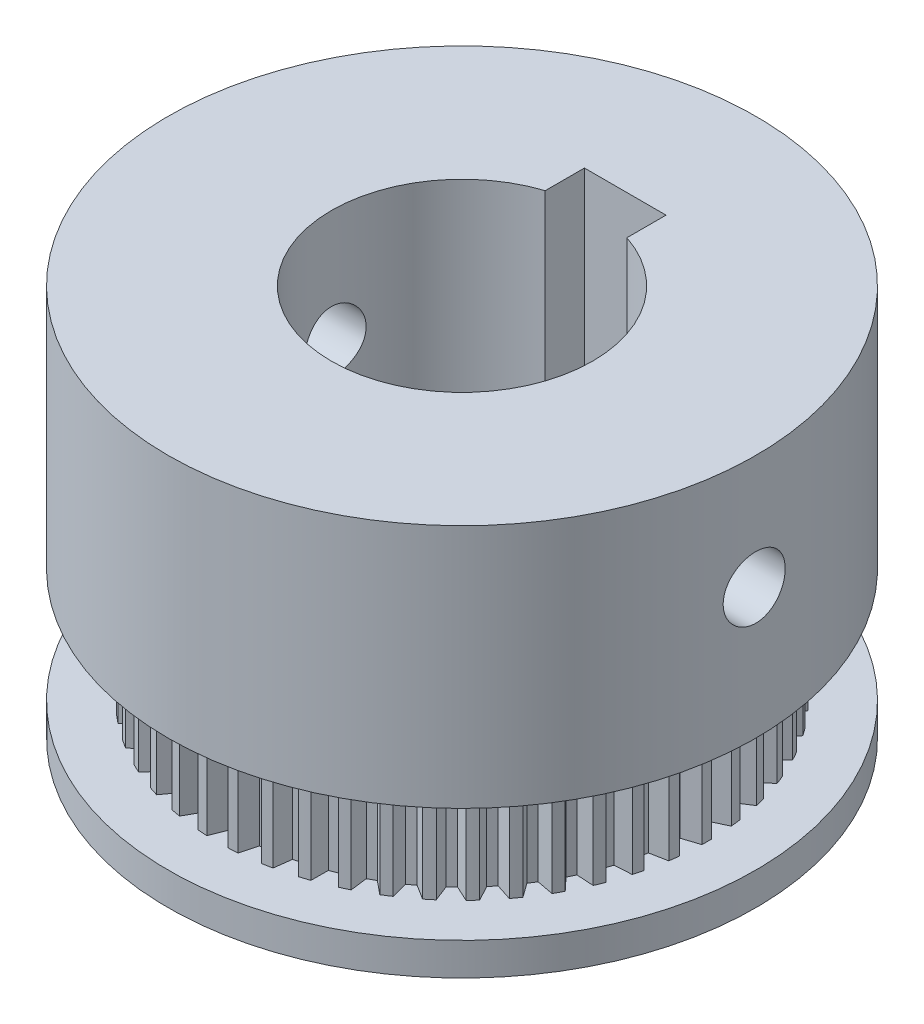
SolidWorks part; units mm, degrees
ref_plane "Front Plane" through (0, 0, 0) normal (0, 0, 1) x (1, 0, 0)
ref_plane "Top Plane" through (0, 0, 0) normal (0, 1, 0) x (1, 0, 0)
ref_plane "Right Plane" through (0, 0, 0) normal (1, 0, 0) x (0, 0, -1)
sketch "Sketch1" plane through (0, 0, 0) normal (0, 1, 0) x (1, 0, 0)
  line L0 (-2.5, 7.5993) -> (-2.5, 10)
  line L1 (-2.5, 10) -> (2.5, 10)
  line L2 (2.5, 10) -> (2.5, 7.5993)
  line L3 (0, -1000) -> (0, 10) construction
  line L4 (-20.8122, -8) -> (34.1524, -8) construction
  line L5 (0, 10) -> (0, 1017.7181) construction
  circle A0 centre (0, 0) radius 15
  arc A1 (-2.5, 7.5993) -> (2.5, 7.5993) centre (0, 0) ccw
  point P13 (0, 9.6034)
  dimension "D1" = 30
  dimension "D2" = 16
  dimension "D3" = 5
  dimension "D4" = 18
extrude "Boss-Extrude1" add sketch "Sketch1" along normal blind 7
sketch "Sketch2" plane through (0, 7, 0) normal (0, 1, 0) x (1, 0, 0)
  line L0 (0, -3.627) -> (0, 5.2187) construction
  line L1 (-0.65, 15) -> (-0.25, 14)
  line L2 (-0.25, 14) -> (0.25, 14)
  line L3 (0.25, 14) -> (0.65, 15)
  line L4 (0.65, 15) -> (-0.65, 15)
  line L5 (1.2351, 14.9632) -> (1.5066, 13.9209)
  line L6 (1.5066, 13.9209) -> (2.0027, 13.8583)
  line L7 (2.0027, 13.8583) -> (2.5249, 14.8003)
  line L8 (2.5249, 14.8003) -> (1.2351, 14.9632)
  line L9 (3.1008, 14.6904) -> (3.2395, 13.6223)
  line L10 (3.2395, 13.6223) -> (3.7238, 13.498)
  line L11 (3.7238, 13.498) -> (4.3599, 14.3671)
  line L12 (4.3599, 14.3671) -> (3.1008, 14.6904)
  line L13 (4.9175, 14.1859) -> (4.9213, 13.1089)
  line L14 (4.9213, 13.1089) -> (5.3862, 12.9248)
  line L15 (5.3862, 12.9248) -> (6.1262, 13.7074)
  line L16 (6.1262, 13.7074) -> (4.9175, 14.1859)
  line L17 (6.6567, 13.4577) -> (6.5255, 12.3887)
  line L18 (6.5255, 12.3887) -> (6.9636, 12.1479)
  line L19 (6.9636, 12.1479) -> (7.7959, 12.8315)
  line L20 (7.7959, 12.8315) -> (6.6567, 13.4577)
  line L21 (8.2909, 12.5173) -> (8.0267, 11.4732)
  line L22 (8.0267, 11.4732) -> (8.4312, 11.1793)
  line L23 (8.4312, 11.1793) -> (9.3426, 11.7532)
  line L24 (9.3426, 11.7532) -> (8.2909, 12.5173)
  line L25 (9.7944, 11.3795) -> (9.4014, 10.3767)
  line L26 (9.4014, 10.3767) -> (9.7659, 10.0344)
  line L27 (9.7659, 10.0344) -> (10.742, 10.4896)
  line L28 (10.742, 10.4896) -> (9.7944, 11.3795)
  line L29 (11.1434, 10.0622) -> (10.6278, 9.1166)
  line L30 (10.6278, 9.1166) -> (10.9465, 8.7313)
  line L31 (10.9465, 8.7313) -> (11.972, 9.0605)
  line L32 (11.972, 9.0605) -> (11.1434, 10.0622)
  line L33 (12.3166, 8.5862) -> (11.6866, 7.7127)
  line L34 (11.6866, 7.7127) -> (11.9545, 7.2905)
  line L35 (11.9545, 7.2905) -> (13.0132, 7.4886)
  line L36 (13.0132, 7.4886) -> (12.3166, 8.5862)
  line L37 (13.2956, 6.9748) -> (12.5611, 6.1871)
  line L38 (12.5611, 6.1871) -> (12.774, 5.7347)
  line L39 (12.774, 5.7347) -> (13.8492, 5.7986)
  line L40 (13.8492, 5.7986) -> (13.2956, 6.9748)
  line L41 (14.065, 5.2534) -> (13.2375, 4.564)
  line L42 (13.2375, 4.564) -> (13.392, 4.0885)
  line L43 (13.392, 4.0885) -> (14.4667, 4.0171)
  line L44 (14.4667, 4.0171) -> (14.065, 5.2534)
  line L45 (14.6125, 3.4492) -> (13.7052, 2.8689)
  line L46 (13.7052, 2.8689) -> (13.7989, 2.3778)
  line L47 (13.7989, 2.3778) -> (14.8561, 2.1722)
  line L48 (14.8561, 2.1722) -> (14.6125, 3.4492)
  line L49 (14.9296, 1.5906) -> (13.9567, 1.1286)
  line L50 (13.9567, 1.1286) -> (13.9881, 0.6296)
  line L51 (13.9881, 0.6296) -> (15.0112, 0.2931)
  line L52 (15.0112, 0.2931) -> (14.9296, 1.5906)
  line L53 (15.0112, -0.2931) -> (13.9881, -0.6296)
  line L54 (13.9881, -0.6296) -> (13.9567, -1.1286)
  line L55 (13.9567, -1.1286) -> (14.9296, -1.5906)
  line L56 (14.9296, -1.5906) -> (15.0112, -0.2931)
  line L57 (14.8561, -2.1722) -> (13.7989, -2.3778)
  line L58 (13.7989, -2.3778) -> (13.7052, -2.8689)
  line L59 (13.7052, -2.8689) -> (14.6125, -3.4492)
  line L60 (14.6125, -3.4492) -> (14.8561, -2.1722)
  line L61 (14.4667, -4.0171) -> (13.392, -4.0885)
  line L62 (13.392, -4.0885) -> (13.2375, -4.564)
  line L63 (13.2375, -4.564) -> (14.065, -5.2534)
  line L64 (14.065, -5.2534) -> (14.4667, -4.0171)
  line L65 (13.8492, -5.7986) -> (12.774, -5.7347)
  line L66 (12.774, -5.7347) -> (12.5611, -6.1871)
  line L67 (12.5611, -6.1871) -> (13.2956, -6.9748)
  line L68 (13.2956, -6.9748) -> (13.8492, -5.7986)
  line L69 (13.0132, -7.4886) -> (11.9545, -7.2905)
  line L70 (11.9545, -7.2905) -> (11.6866, -7.7127)
  line L71 (11.6866, -7.7127) -> (12.3166, -8.5862)
  line L72 (12.3166, -8.5862) -> (13.0132, -7.4886)
  line L73 (11.972, -9.0605) -> (10.9465, -8.7313)
  line L74 (10.9465, -8.7313) -> (10.6278, -9.1166)
  line L75 (10.6278, -9.1166) -> (11.1434, -10.0622)
  line L76 (11.1434, -10.0622) -> (11.972, -9.0605)
  line L77 (10.742, -10.4896) -> (9.7659, -10.0344)
  line L78 (9.7659, -10.0344) -> (9.4014, -10.3767)
  line L79 (9.4014, -10.3767) -> (9.7944, -11.3795)
  line L80 (9.7944, -11.3795) -> (10.742, -10.4896)
  line L81 (9.3426, -11.7532) -> (8.4312, -11.1793)
  line L82 (8.4312, -11.1793) -> (8.0267, -11.4732)
  line L83 (8.0267, -11.4732) -> (8.2909, -12.5173)
  line L84 (8.2909, -12.5173) -> (9.3426, -11.7532)
  line L85 (7.7959, -12.8315) -> (6.9636, -12.1479)
  line L86 (6.9636, -12.1479) -> (6.5255, -12.3887)
  line L87 (6.5255, -12.3887) -> (6.6567, -13.4577)
  line L88 (6.6567, -13.4577) -> (7.7959, -12.8315)
  line L89 (6.1262, -13.7074) -> (5.3862, -12.9248)
  line L90 (5.3862, -12.9248) -> (4.9213, -13.1089)
  line L91 (4.9213, -13.1089) -> (4.9175, -14.1859)
  line L92 (4.9175, -14.1859) -> (6.1262, -13.7074)
  line L93 (4.3599, -14.3671) -> (3.7238, -13.498)
  line L94 (3.7238, -13.498) -> (3.2395, -13.6223)
  line L95 (3.2395, -13.6223) -> (3.1008, -14.6904)
  line L96 (3.1008, -14.6904) -> (4.3599, -14.3671)
  line L97 (2.5249, -14.8003) -> (2.0027, -13.8583)
  line L98 (2.0027, -13.8583) -> (1.5066, -13.9209)
  line L99 (1.5066, -13.9209) -> (1.2351, -14.9632)
  line L100 (1.2351, -14.9632) -> (2.5249, -14.8003)
  line L101 (0.65, -15) -> (0.25, -14)
  line L102 (0.25, -14) -> (-0.25, -14)
  line L103 (-0.25, -14) -> (-0.65, -15)
  line L104 (-0.65, -15) -> (0.65, -15)
  line L105 (-1.2351, -14.9632) -> (-1.5066, -13.9209)
  line L106 (-1.5066, -13.9209) -> (-2.0027, -13.8583)
  line L107 (-2.0027, -13.8583) -> (-2.5249, -14.8003)
  line L108 (-2.5249, -14.8003) -> (-1.2351, -14.9632)
  line L109 (-3.1008, -14.6904) -> (-3.2395, -13.6223)
  line L110 (-3.2395, -13.6223) -> (-3.7238, -13.498)
  line L111 (-3.7238, -13.498) -> (-4.3599, -14.3671)
  line L112 (-4.3599, -14.3671) -> (-3.1008, -14.6904)
  line L113 (-4.9175, -14.1859) -> (-4.9213, -13.1089)
  line L114 (-4.9213, -13.1089) -> (-5.3862, -12.9248)
  line L115 (-5.3862, -12.9248) -> (-6.1262, -13.7074)
  line L116 (-6.1262, -13.7074) -> (-4.9175, -14.1859)
  line L117 (-6.6567, -13.4577) -> (-6.5255, -12.3887)
  line L118 (-6.5255, -12.3887) -> (-6.9636, -12.1479)
  line L119 (-6.9636, -12.1479) -> (-7.7959, -12.8315)
  line L120 (-7.7959, -12.8315) -> (-6.6567, -13.4577)
  line L121 (-8.2909, -12.5173) -> (-8.0267, -11.4732)
  line L122 (-8.0267, -11.4732) -> (-8.4312, -11.1793)
  line L123 (-8.4312, -11.1793) -> (-9.3426, -11.7532)
  line L124 (-9.3426, -11.7532) -> (-8.2909, -12.5173)
  line L125 (-9.7944, -11.3795) -> (-9.4014, -10.3767)
  line L126 (-9.4014, -10.3767) -> (-9.7659, -10.0344)
  line L127 (-9.7659, -10.0344) -> (-10.742, -10.4896)
  line L128 (-10.742, -10.4896) -> (-9.7944, -11.3795)
  line L129 (-11.1434, -10.0622) -> (-10.6278, -9.1166)
  line L130 (-10.6278, -9.1166) -> (-10.9465, -8.7313)
  line L131 (-10.9465, -8.7313) -> (-11.972, -9.0605)
  line L132 (-11.972, -9.0605) -> (-11.1434, -10.0622)
  line L133 (-12.3166, -8.5862) -> (-11.6866, -7.7127)
  line L134 (-11.6866, -7.7127) -> (-11.9545, -7.2905)
  line L135 (-11.9545, -7.2905) -> (-13.0132, -7.4886)
  line L136 (-13.0132, -7.4886) -> (-12.3166, -8.5862)
  line L137 (-13.2956, -6.9748) -> (-12.5611, -6.1871)
  line L138 (-12.5611, -6.1871) -> (-12.774, -5.7347)
  line L139 (-12.774, -5.7347) -> (-13.8492, -5.7986)
  line L140 (-13.8492, -5.7986) -> (-13.2956, -6.9748)
  line L141 (-14.065, -5.2534) -> (-13.2375, -4.564)
  line L142 (-13.2375, -4.564) -> (-13.392, -4.0885)
  line L143 (-13.392, -4.0885) -> (-14.4667, -4.0171)
  line L144 (-14.4667, -4.0171) -> (-14.065, -5.2534)
  line L145 (-14.6125, -3.4492) -> (-13.7052, -2.8689)
  line L146 (-13.7052, -2.8689) -> (-13.7989, -2.3778)
  line L147 (-13.7989, -2.3778) -> (-14.8561, -2.1722)
  line L148 (-14.8561, -2.1722) -> (-14.6125, -3.4492)
  line L149 (-14.9296, -1.5906) -> (-13.9567, -1.1286)
  line L150 (-13.9567, -1.1286) -> (-13.9881, -0.6296)
  line L151 (-13.9881, -0.6296) -> (-15.0112, -0.2931)
  line L152 (-15.0112, -0.2931) -> (-14.9296, -1.5906)
  line L153 (-15.0112, 0.2931) -> (-13.9881, 0.6296)
  line L154 (-13.9881, 0.6296) -> (-13.9567, 1.1286)
  line L155 (-13.9567, 1.1286) -> (-14.9296, 1.5906)
  line L156 (-14.9296, 1.5906) -> (-15.0112, 0.2931)
  line L157 (-14.8561, 2.1722) -> (-13.7989, 2.3778)
  line L158 (-13.7989, 2.3778) -> (-13.7052, 2.8689)
  line L159 (-13.7052, 2.8689) -> (-14.6125, 3.4492)
  line L160 (-14.6125, 3.4492) -> (-14.8561, 2.1722)
  line L161 (-14.4667, 4.0171) -> (-13.392, 4.0885)
  line L162 (-13.392, 4.0885) -> (-13.2375, 4.564)
  line L163 (-13.2375, 4.564) -> (-14.065, 5.2534)
  line L164 (-14.065, 5.2534) -> (-14.4667, 4.0171)
  line L165 (-13.8492, 5.7986) -> (-12.774, 5.7347)
  line L166 (-12.774, 5.7347) -> (-12.5611, 6.1871)
  line L167 (-12.5611, 6.1871) -> (-13.2956, 6.9748)
  line L168 (-13.2956, 6.9748) -> (-13.8492, 5.7986)
  line L169 (-13.0132, 7.4886) -> (-11.9545, 7.2905)
  line L170 (-11.9545, 7.2905) -> (-11.6866, 7.7127)
  line L171 (-11.6866, 7.7127) -> (-12.3166, 8.5862)
  line L172 (-12.3166, 8.5862) -> (-13.0132, 7.4886)
  line L173 (-11.972, 9.0605) -> (-10.9465, 8.7313)
  line L174 (-10.9465, 8.7313) -> (-10.6278, 9.1166)
  line L175 (-10.6278, 9.1166) -> (-11.1434, 10.0622)
  line L176 (-11.1434, 10.0622) -> (-11.972, 9.0605)
  line L177 (-10.742, 10.4896) -> (-9.7659, 10.0344)
  line L178 (-9.7659, 10.0344) -> (-9.4014, 10.3767)
  line L179 (-9.4014, 10.3767) -> (-9.7944, 11.3795)
  line L180 (-9.7944, 11.3795) -> (-10.742, 10.4896)
  line L181 (-9.3426, 11.7532) -> (-8.4312, 11.1793)
  line L182 (-8.4312, 11.1793) -> (-8.0267, 11.4732)
  line L183 (-8.0267, 11.4732) -> (-8.2909, 12.5173)
  line L184 (-8.2909, 12.5173) -> (-9.3426, 11.7532)
  line L185 (-7.7959, 12.8315) -> (-6.9636, 12.1479)
  line L186 (-6.9636, 12.1479) -> (-6.5255, 12.3887)
  line L187 (-6.5255, 12.3887) -> (-6.6567, 13.4577)
  line L188 (-6.6567, 13.4577) -> (-7.7959, 12.8315)
  line L189 (-6.1262, 13.7074) -> (-5.3862, 12.9248)
  line L190 (-5.3862, 12.9248) -> (-4.9213, 13.1089)
  line L191 (-4.9213, 13.1089) -> (-4.9175, 14.1859)
  line L192 (-4.9175, 14.1859) -> (-6.1262, 13.7074)
  line L193 (-4.3599, 14.3671) -> (-3.7238, 13.498)
  line L194 (-3.7238, 13.498) -> (-3.2395, 13.6223)
  line L195 (-3.2395, 13.6223) -> (-3.1008, 14.6904)
  line L196 (-3.1008, 14.6904) -> (-4.3599, 14.3671)
  line L197 (-2.5249, 14.8003) -> (-2.0027, 13.8583)
  line L198 (-2.0027, 13.8583) -> (-1.5066, 13.9209)
  line L199 (-1.5066, 13.9209) -> (-1.2351, 14.9632)
  line L200 (-1.2351, 14.9632) -> (-2.5249, 14.8003)
  circle A2 centre (0, 0) radius 15 construction
  point P10 (0, 15)
  point P11 (0, 14)
  point P210 (0, 0)
  dimension "D1" = 1
  dimension "D2" = 1.3
  dimension "D3" = 0.5
  dimension "D4" = 50
extrude "Cut-Extrude1" cut sketch "Sketch2" against normal through all
sketch "Sketch3" plane through (0, 0, 0) normal (0, -1, 0) x (1, 0, 0)
  line L0 (-2.5, -7.5993) -> (-2.5, -10)
  line L1 (-2.5, -10) -> (2.5, -10)
  line L2 (2.5, -10) -> (2.5, -7.5993)
  arc A0 (2.5, -7.5993) -> (-2.5, -7.5993) centre (0, 0) ccw
  circle A1 centre (0, 0) radius 18
  dimension "D1" = 36
extrude "Boss-Extrude2" add sketch "Sketch3" along normal blind 2
sketch "Sketch4" plane through (0, 7, 0) normal (0, 1, 0) x (1, 0, 0)
  line L0 (-2.5, 7.5993) -> (-2.5, 10)
  line L1 (-2.5, 10) -> (2.5, 10)
  line L2 (2.5, 10) -> (2.5, 7.5993)
  line L3 (2.5, 7.5993) -> (2.5, 10) construction
  circle A0 centre (0, 0) radius 18
  circle A1 centre (0, 0) radius 18 construction
  arc A2 (-2.5, 7.5993) -> (2.5, 7.5993) centre (0, 0) ccw construction
  arc A3 (2.5, 7.5993) -> (-2.5, 7.5993) centre (0, 0) cw
  point P18 (0, 0)
  point P19 (-2.8245, 7.4848)
extrude "Boss-Extrude3" add sketch "Sketch4" along normal blind 15
sketch "Sketch5" plane through (0, 0, 0) normal (1, 0, 0) x (0, 0, -1)
  circle A0 centre (0, 15) radius 1.9
  point P2 (0, 0)
  dimension "D1" = 3.8
  dimension "D2" = 15
extrude "Cut-Extrude2" cut sketch "Sketch5" against normal through all and the other way through all
